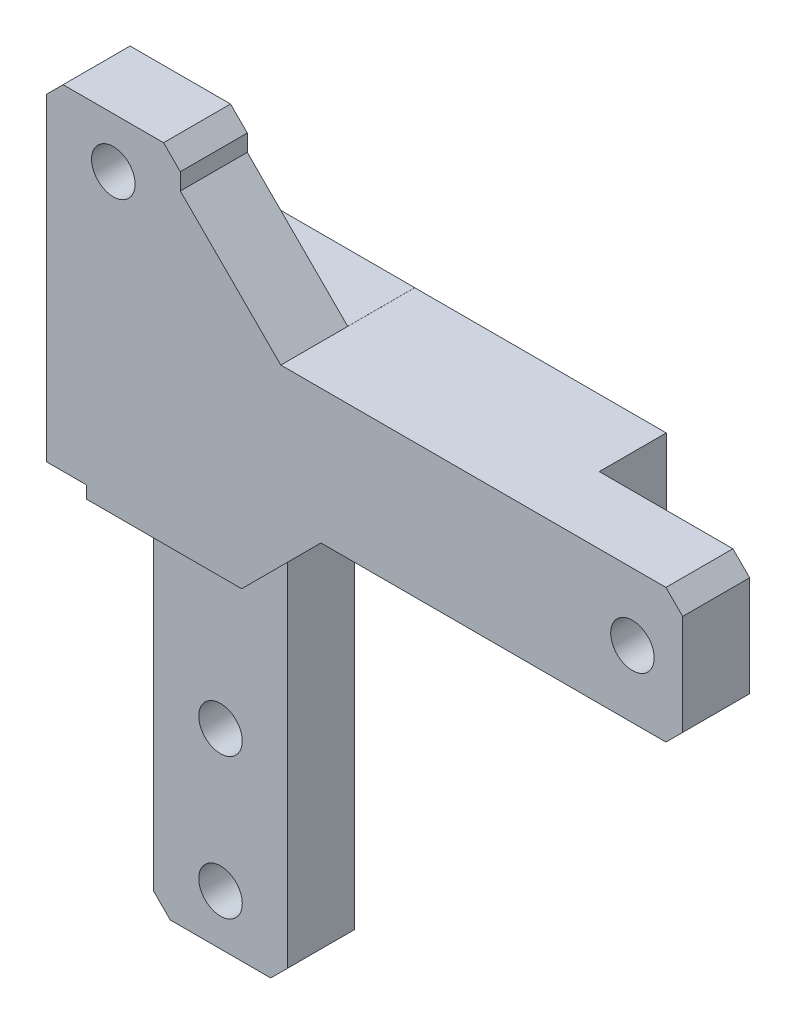
SolidWorks part; units mm, degrees
ref_plane "前视基准面" through (0, 0, 0) normal (0, 0, 1) x (1, 0, 0)
ref_plane "上视基准面" through (0, 0, 0) normal (0, 1, 0) x (1, 0, 0)
ref_plane "右视基准面" through (0, 0, 0) normal (1, 0, 0) x (0, 0, -1)
other "Configuration Table"
sketch "草图1" plane through (0, 0, 0) normal (0, 0, 1) x (1, 0, 0)
  line L0 (-4.3, -2.5) -> (9.5, -2.5)
  line L1 (-5.5, 1.5) -> (9.5, 1.5)
  line L4 (9.5, 1.5) -> (9.5, -2.5)
  line L8 (-9.5, 1.5) -> (-9.5, 5.5)
  line L9 (-9.5, 5.5) -> (-5.5, 5.5)
  line L11 (-5.5, 1.5) -> (-5.5, 5.5)
  line L12 (-9.5, 1.5) -> (-9.5, -4.5)
  line L13 (-8.3, -4.5) -> (-8.3, -16.5)
  line L14 (-8.3, -16.5) -> (-4.3, -16.5)
  line L15 (-4.3, -16.5) -> (-4.3, -2.5)
  line L16 (-9.5, -4.5) -> (-8.3, -4.5)
  circle A0 centre (8, -0.5) radius 0.65
  circle A1 centre (-7.5, 4) radius 0.65
  circle A2 centre (-6.3, -15) radius 0.65
  circle A3 centre (-6.3, -10.8) radius 0.65
  point P0 (0, 0)
  dimension "D3" = 1.3
  dimension "D8" = 1.3
  dimension "D15" = 1.3
  dimension "D16" = 1.3
  dimension "D2" = 6
  dimension "D4" = 2
  dimension "D5" = 1.5
  dimension "D6" = 10
  dimension "D7" = 4
  dimension "D9" = 2
  dimension "D10" = 1.5
  dimension "D11" = 4
  dimension "D12" = 4
  dimension "D13" = 2
  dimension "D14" = 19
  dimension "D17" = 4.2
  dimension "D18" = 1.5
  dimension "D19" = 2
extrude "凸台-拉伸1" add sketch "草图1" along normal blind 4
sketch "草图2" plane through (0, 0, 4) normal (0, 0, 1) x (1, 0, 0)
  line L0 (-8.3, -4.8687) -> (-4.3, -4.8687)
  line L10 (9.5, -2.5) -> (9.5, 1.5)
  line L11 (9.5, 1.5) -> (-5.5, 1.5)
  line L12 (-5.5, 1.5) -> (-5.5, 5.5)
  line L13 (-5.5, 5.5) -> (-9.5, 5.5)
  line L14 (-9.5, 5.5) -> (-9.5, -4.5)
  line L15 (-9.5, -4.5) -> (-8.3, -4.5)
  line L16 (-8.3, -4.5) -> (-8.3, -16.5)
  line L17 (-8.3, -16.5) -> (-4.3, -16.5)
  line L18 (-4.3, -16.5) -> (-4.3, -2.5)
  line L19 (-4.3, -2.5) -> (9.5, -2.5)
  line L26 (-8.3, -4.8687) -> (-8.3, -16.5)
  line L27 (-8.3, -16.5) -> (-4.3, -16.5)
  line L28 (-4.3, -16.5) -> (-4.3, -4.8687)
  circle A0 centre (-6.3, -15) radius 0.65 construction
  circle A1 centre (-6.3, -10.8) radius 0.65 construction
  circle A2 centre (-6.3, -15) radius 0.65
  circle A3 centre (-6.3, -10.8) radius 0.65
  dimension "D1" = 0
extrude "切除-拉伸1" cut sketch "草图2" against normal blind 2
sketch "草图3" plane through (0, 0, 0) normal (0, 0, -1) x (-1, 0, 0)
  line L0 (-5.0101, 1.5) -> (-5.0101, -2.5)
  line L1 (5.5, 1.5011) -> (9.5, 1.5011)
  line L10 (-9.5, 1.5) -> (-9.5, -2.5)
  line L11 (-9.5, -2.5) -> (4.3, -2.5)
  line L12 (4.3, -2.5) -> (4.3, -16.5)
  line L13 (4.3, -16.5) -> (8.3, -16.5)
  line L14 (8.3, -16.5) -> (8.3, -4.5)
  line L15 (8.3, -4.5) -> (9.5, -4.5)
  line L16 (9.5, -4.5) -> (9.5, 5.5)
  line L17 (9.5, 5.5) -> (5.5, 5.5)
  line L18 (5.5, 5.5) -> (5.5, 1.5)
  line L19 (5.5, 1.5) -> (-9.5, 1.5)
  line L20 (-9.5, 1.5) -> (-9.5, -2.5)
  line L21 (-9.5, -2.5) -> (-5.0101, -2.5)
  line L26 (9.5, 1.5011) -> (9.5, 5.5)
  line L27 (9.5, 5.5) -> (5.5, 5.5)
  line L28 (5.5, 5.5) -> (5.5, 1.5011)
  line L29 (-5.0101, 1.5) -> (-9.5, 1.5)
  circle A0 centre (-8, -0.5) radius 0.65 construction
  circle A1 centre (7.5, 4) radius 0.65 construction
  circle A2 centre (-8, -0.5) radius 0.65
  circle A3 centre (7.5, 4) radius 0.65
  dimension "D1" = 0
extrude "切除-拉伸2" cut sketch "草图3" against normal blind 2
chamfer "倒角1" distance 3 angle 45 2 edges at (-4.3, -2.5, 2) (-5.5, 1.5, 2)
chamfer "倒角2" distance 0.5 angle 45 6 edges at (-4.3, -16.5, 1) (-8.3, -16.5, 1) (-9.5, 5.5, 3) (9.5, -2.5, 3) (9.5, 1.5, 3) (-5.5, 5.5, 3)
